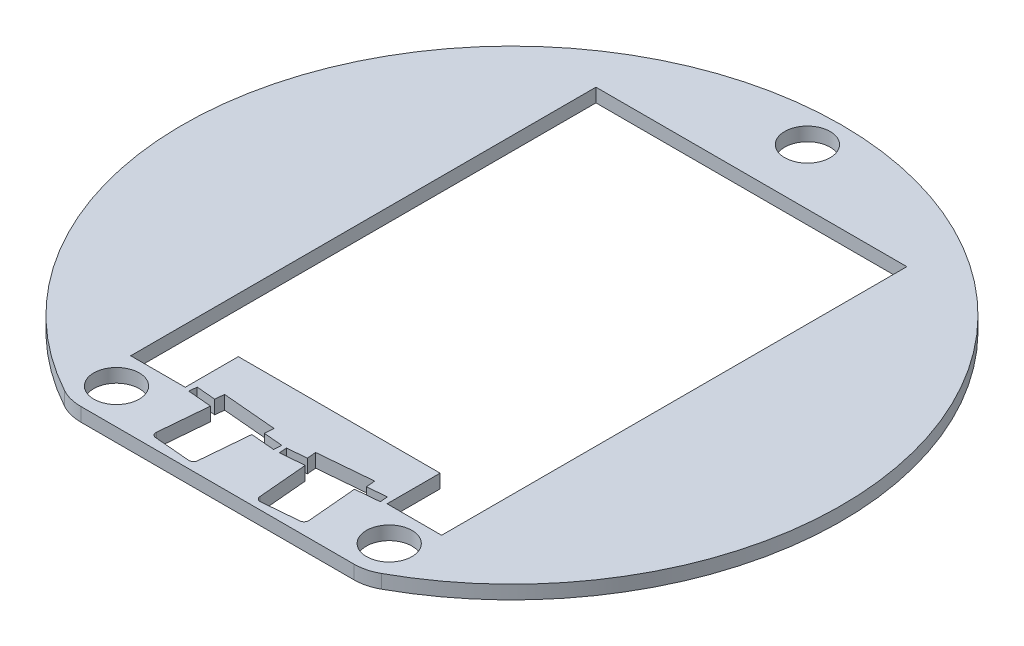
SolidWorks part; units mm, degrees
ref_plane "Front Plane" through (0, 0, 0) normal (0, 0, 1) x (1, 0, 0)
ref_plane "Top Plane" through (0, 0, 0) normal (0, 1, 0) x (1, 0, 0)
ref_plane "Right Plane" through (0, 0, 0) normal (1, 0, 0) x (0, 0, -1)
sketch "Sketch1" plane through (0, 0, 0) normal (0, 1, 0) x (1, 0, 0)
  line L0 (-30.03, -64.8129) -> (30.03, -64.8129)
  line L1 (0, -85) -> (0, 0) construction
  line L2 (0, -85) -> (32.4891, -64.8129) construction
  arc A0 (34.8348, -63.5829) -> (-34.8348, -63.5829) centre (0, 0) ccw
  circle A1 centre (0, -85) radius 38.25 construction
  arc A2 (30.03, -64.8129) -> (34.8348, -63.5829) centre (30.03, -54.8129) ccw
  arc A3 (-30.03, -64.8129) -> (-34.8348, -63.5829) centre (-30.03, -54.8129) cw
  dimension "D1" = 145
  dimension "D2" = 76.5
  dimension "D4" = 10
  dimension "D3" = 85
extrude "Boss-Extrude1" add sketch "Sketch1" along normal blind 3
sketch "Sketch2" plane through (0, 3, 0) normal (0, 1, 0) x (1, 0, 0)
  line L29 (-22.2, -49.6757) -> (-22.2, -32.5) construction
  line L30 (-22.2, -49.6757) -> (-22.2, -32.5) construction
  line L38 (-34.2, -49.6757) -> (-22.2, -49.6757) construction
  line L39 (-34.2, -49.6757) -> (-34.2, 49.6757) construction
  line L40 (-34.2, 49.6757) -> (-22.2, 49.6757) construction
  line L41 (-22.2, 32.5) -> (-22.2, 49.6757) construction
  line L47 (22.2, 32.5) -> (22.2, 49.6757) construction
  line L48 (34.2, 49.6757) -> (22.2, 49.6757) construction
  line L49 (34.2, -49.6757) -> (34.2, 49.6757) construction
  line L50 (34.2, -49.6757) -> (22.2, -49.6757) construction
  line L51 (22.2, -49.6757) -> (22.2, -32.5) construction
  line L52 (22.2, -49.6757) -> (22.2, -32.5) construction
  line L53 (-22.2, -49.6757) -> (-22.2, -38) construction
  line L54 (-22.2, -49.6757) -> (-22.2, -38)
  line L55 (-22.2, 44) -> (22.2, 44)
  line L62 (-34.2, -49.6757) -> (-22.2, -49.6757)
  line L63 (-34.2, -49.6757) -> (-34.2, 49.6757)
  line L64 (-34.2, 49.6757) -> (-22.2, 49.6757)
  line L65 (-22.2, 44) -> (-22.2, 49.6757)
  line L71 (22.2, 44) -> (22.2, 49.6757)
  line L72 (34.2, 49.6757) -> (22.2, 49.6757)
  line L73 (34.2, -49.6757) -> (34.2, 49.6757)
  line L74 (34.2, -49.6757) -> (22.2, -49.6757)
  line L75 (22.2, -49.6757) -> (22.2, -38) construction
  line L76 (22.2, -49.6757) -> (22.2, -38)
  line L77 (-22.2, -38) -> (22.2, -38)
  dimension "D1" = 38
  dimension "D2" = 44
extrude "Cut-Extrude1" cut sketch "Sketch2" against normal through all
sketch "Sketch3" plane through (0, 3, 0) normal (0, 1, 0) x (1, 0, 0)
  line L0 (-34.2, 35) -> (-34.2, -35)
  line L1 (-72.5, -35) -> (-34.2, -35)
  line L2 (-72.5, -35) -> (-72.5, 35)
  line L3 (-72.5, 35) -> (-34.2, 35)
  line L4 (72.5, -35) -> (72.5, 35)
  line L5 (-72.5, -35) -> (72.5, 35) construction
  line L6 (-72.5, 35) -> (72.5, -35) construction
  line L8 (34.2, 35) -> (34.2, -35)
  line L10 (34.2, 35) -> (72.5, 35)
  line L11 (34.2, -35) -> (72.5, -35)
  line L12 (-34.2, -49.6757) -> (-34.2, 49.6757) construction
  line L13 (34.2, -49.6757) -> (34.2, 49.6757) construction
  arc A0 (34.8348, -63.5829) -> (-34.8348, -63.5829) centre (0, 0) ccw construction
  point P0 (0, 0)
  dimension "D1" = 70
sketch "Sketch4" plane through (0, 3, 0) normal (0, 1, 0) x (1, 0, 0)
  line L0 (-21.0702, -50.0262) -> (-0.6482, -51.8129)
  line L1 (21.0702, -50.0262) -> (20.922, -48.3326)
  line L2 (0.6482, -51.8129) -> (0.5, -50.1193)
  line L3 (20.922, -48.3326) -> (0.5, -50.1193)
  line L4 (0, 0) -> (0, -64.8129) construction
  line L5 (-30.03, -64.8129) -> (30.03, -64.8129) construction
  line L6 (-20.922, -48.3326) -> (-0.5, -50.1193)
  line L7 (-0.6482, -51.8129) -> (-0.5, -50.1193)
  line L8 (-21.0702, -50.0262) -> (-20.922, -48.3326)
  line L14 (21.0702, -50.0262) -> (0.6482, -51.8129)
  dimension "D1" = 1.7
  dimension "D2" = 20.5
  dimension "D3" = 5
  dimension "D4" = 13
  dimension "D5" = 0.5
extrude "Cut-Extrude3" cut sketch "Sketch4" against normal through all
sketch "Sketch5" plane through (0, 3, 0) normal (0, 1, 0) x (1, 0, 0)
  line L0 (5.8782, -51.3553) -> (15.8401, -50.4837)
  line L1 (5.8782, -51.3553) -> (6.8369, -62.3134)
  line L2 (15.8401, -50.4837) -> (16.7988, -61.4419)
  line L3 (7.9203, -63.2225) -> (15.8898, -62.5252)
  line L4 (0.6482, -51.8129) -> (21.0702, -50.0262) construction
  line L5 (16.6882, -48.7031) -> (4.7338, -49.7489)
  line L6 (16.6882, -48.7031) -> (16.5139, -46.7107)
  line L7 (4.7338, -49.7489) -> (4.5595, -47.7565)
  line L8 (16.5139, -46.7107) -> (4.5595, -47.7565)
  line L9 (20.922, -48.3326) -> (0.5, -50.1193) construction
  line L10 (0, -38) -> (0, -64.8129) construction
  line L12 (-30.03, -64.8129) -> (30.03, -64.8129) construction
  line L13 (-16.5139, -46.7107) -> (-4.5595, -47.7565)
  line L14 (-4.7338, -49.7489) -> (-4.5595, -47.7565)
  line L15 (-16.6882, -48.7031) -> (-16.5139, -46.7107)
  line L16 (-16.6882, -48.7031) -> (-4.7338, -49.7489)
  line L17 (-7.9203, -63.2225) -> (-15.8898, -62.5252)
  line L18 (-15.8401, -50.4837) -> (-16.7988, -61.4419)
  line L19 (-5.8782, -51.3553) -> (-6.8369, -62.3134)
  line L20 (-5.8782, -51.3553) -> (-15.8401, -50.4837)
  line L21 (-22.2, -38) -> (22.2, -38) construction
  arc A0 (16.7988, -61.4419) -> (15.8898, -62.5252) centre (15.8027, -61.529) cw
  arc A1 (6.8369, -62.3134) -> (7.9203, -63.2225) centre (7.8331, -62.2263) ccw
  arc A2 (-6.8369, -62.3134) -> (-7.9203, -63.2225) centre (-7.8331, -62.2263) cw
  arc A3 (-16.7988, -61.4419) -> (-15.8898, -62.5252) centre (-15.8027, -61.529) ccw
  point P14 (10.711, -49.226)
  point P15 (10.711, -49.226)
  point P17 (10.8592, -50.9195)
  point P18 (10.8592, -50.9195)
  point P21 (16.886, -62.4381)
  point P24 (6.9241, -63.3096)
  point P40 (-6.9241, -63.3096)
  point P41 (-16.886, -62.4381)
  dimension "D5" = 1
  dimension "D1" = 12
  dimension "D2" = 10
  dimension "D3" = 12
  dimension "D4" = 2
extrude "Cut-Extrude4" cut sketch "Sketch5" against normal through all
sketch "Sketch6" plane through (0, 3, 0) normal (0, 1, 0) x (1, 0, 0)
  line L2 (-34.2, 49.6757) -> (34.2, 49.6757)
  line L3 (-34.2, 49.6757) -> (-34.2, 52.6757)
  line L4 (-34.2, 52.6757) -> (34.2, 52.6757)
  line L5 (34.2, 49.6757) -> (34.2, 52.6757)
  dimension "D1" = 3
extrude "Cut-Extrude5" cut sketch "Sketch6" against normal through all
sketch "Sketch7" plane through (0, 3, 0) normal (0, 1, 0) x (1, 0, 0)
  circle A1 centre (-30, -57) radius 5
  circle A2 centre (-30, -57) radius 5
  circle A3 centre (30, -57) radius 5
  circle A4 centre (30, -57) radius 5
  dimension "D1" = 0
  dimension "D2" = 0
extrude "Cut-Extrude6" cut sketch "Sketch7" against normal through all
sketch "Sketch8" plane through (0, 3, 0) normal (0, 1, 0) x (1, 0, 0)
  line L10 (-52.7, 37.2865) -> (-52.7, 32.5)
  line L11 (-52.7, 32.5) -> (-43.3, 32.5)
  line L12 (-43.3, 32.5) -> (-43.3, 37.2865)
  line L13 (-43.3, 37.2865) -> (-43.3, 42.7135)
  line L14 (-43.3, 42.7135) -> (-48, 45.4271)
  line L15 (-48, 45.4271) -> (-52.7, 42.7135)
  line L16 (-52.7, 42.7135) -> (-52.7, 37.2865)
  line L17 (-52.7, 37.2865) -> (-52.7, 32.5)
  line L18 (-52.7, 32.5) -> (-43.3, 32.5)
  line L19 (-43.3, 32.5) -> (-43.3, 37.2865)
  line L20 (-43.3, 37.2865) -> (-43.3, 42.7135)
  line L21 (-43.3, 42.7135) -> (-48, 45.4271)
  line L22 (-48, 45.4271) -> (-52.7, 42.7135)
  line L23 (-52.7, 42.7135) -> (-52.7, 37.2865)
  line L24 (44.7, -32.5) -> (35.3, -32.5)
  line L25 (44.7, -37.2865) -> (44.7, -32.5)
  line L26 (44.7, -42.7135) -> (44.7, -37.2865)
  line L31 (40, -45.4271) -> (44.7, -42.7135)
  line L32 (35.3, -42.7135) -> (40, -45.4271)
  line L33 (35.3, -37.2865) -> (35.3, -42.7135)
  line L34 (35.3, -32.5) -> (35.3, -37.2865)
  line L35 (44.7, -32.5) -> (35.3, -32.5)
  line L36 (44.7, -37.2865) -> (44.7, -32.5)
  line L37 (44.7, -42.7135) -> (44.7, -37.2865)
  line L38 (40, -45.4271) -> (44.7, -42.7135)
  line L39 (35.3, -42.7135) -> (40, -45.4271)
  line L40 (35.3, -37.2865) -> (35.3, -42.7135)
  line L41 (35.3, -32.5) -> (35.3, -37.2865)
  line L42 (-35.3, -37.2865) -> (-35.3, -32.5)
  line L43 (-35.3, -32.5) -> (-44.7, -32.5)
  line L44 (-44.7, -32.5) -> (-44.7, -37.2865)
  line L45 (-44.7, -37.2865) -> (-44.7, -42.7135)
  line L46 (-44.7, -42.7135) -> (-40, -45.4271)
  line L47 (-40, -45.4271) -> (-35.3, -42.7135)
  line L48 (-35.3, -42.7135) -> (-35.3, -37.2865)
  line L49 (-35.3, -37.2865) -> (-35.3, -32.5)
  line L50 (-35.3, -32.5) -> (-44.7, -32.5)
  line L51 (-44.7, -32.5) -> (-44.7, -37.2865)
  line L52 (-44.7, -37.2865) -> (-44.7, -42.7135)
  line L53 (-44.7, -42.7135) -> (-40, -45.4271)
  line L54 (-40, -45.4271) -> (-35.3, -42.7135)
  line L55 (-35.3, -42.7135) -> (-35.3, -37.2865)
  line L56 (52.7, 32.5) -> (52.7, 37.2865)
  line L57 (52.7, 37.2865) -> (52.7, 42.7135)
  line L58 (52.7, 42.7135) -> (48, 45.4271)
  line L59 (48, 45.4271) -> (43.3, 42.7135)
  line L60 (43.3, 42.7135) -> (43.3, 37.2865)
  line L61 (43.3, 37.2865) -> (43.3, 32.5)
  line L62 (43.3, 32.5) -> (52.7, 32.5)
  line L63 (52.7, 32.5) -> (52.7, 37.2865)
  line L64 (52.7, 37.2865) -> (52.7, 42.7135)
  line L65 (52.7, 42.7135) -> (48, 45.4271)
  line L66 (48, 45.4271) -> (43.3, 42.7135)
  line L67 (43.3, 42.7135) -> (43.3, 37.2865)
  line L68 (43.3, 37.2865) -> (43.3, 32.5)
  line L69 (43.3, 32.5) -> (52.7, 32.5)
  dimension "D1" = 0
  dimension "D2" = 0
  dimension "D3" = 0
  dimension "D4" = 0
extrude "Cut-Extrude7" [suppressed] cut sketch "Sketch8" against normal through all
sketch "Sketch11" plane through (0, 3, 0) normal (0, 1, 0) x (1, 0, 0)
  line L0 (0, 0) -> (0, 65) construction
  circle A0 centre (0, 65) radius 5
  dimension "D2" = 10
  dimension "D1" = 65
extrude "Cut-Extrude10" cut sketch "Sketch11" against normal through all
sketch "Sketch12" plane through (0, 3, 0) normal (0, 1, 0) x (1, 0, 0)
  line L0 (-30.03, -64.8129) -> (30.03, -64.8129) construction
  line L1 (-1.35, -64.8129) -> (1.35, -64.8129)
  line L2 (-1.35, -64.8129) -> (-1.35, -61.8129)
  line L3 (-1.35, -55.8129) -> (1.35, -55.8129)
  line L4 (1.35, -64.8129) -> (1.35, -61.8129)
  line L5 (-1.35, -59.6129) -> (-3.1, -59.6129)
  line L6 (3.1, -59.6129) -> (1.35, -59.6129)
  line L7 (3.1, -59.6129) -> (3.1, -61.8129)
  line L8 (3.1, -61.8129) -> (1.35, -61.8129)
  line L9 (-3.1, -59.6129) -> (-3.1, -61.8129)
  line L10 (-1.35, -61.8129) -> (-3.1, -61.8129)
  line L11 (-1.35, -59.6129) -> (-1.35, -55.8129)
  line L12 (1.35, -59.6129) -> (1.35, -55.8129)
  point P14 (0, -64.8129)
  point P15 (0, -64.8129)
  dimension "D1" = 3
  dimension "D2" = 9
  dimension "D3" = 2.7
  dimension "D4" = 2.2
  dimension "D5" = 6.2
extrude "Cut-Extrude11" [suppressed] cut sketch "Sketch12" against normal through all
sketch "Sketch13" plane through (0, 3, 0) normal (0, 1, 0) x (1, 0, 0)
  line L0 (0, 0) -> (0, -22.8942) construction
  circle A0 centre (45, -48) radius 1.65
  circle A1 centre (-45, -48) radius 1.65
  circle A2 centre (40, 50) radius 1.65
  circle A3 centre (-40, 50) radius 1.65
  dimension "D3" = 3.3
  dimension "D1" = 48
  dimension "D2" = 45
  dimension "D4" = 40
  dimension "D5" = 50
extrude "Cut-Extrude12" [suppressed] cut sketch "Sketch13" against normal through all
sketch "Sketch14" plane through (0, 0, 0) normal (0, -1, 0) x (1, 0, 0)
  line L8 (-41.543, 56.9759) -> (-42.0754, 56.6031)
  line L9 (-42.0754, 56.6031) -> (-40.0679, 53.736)
  line L10 (-40.0679, 53.736) -> (-36.7913, 56.0303)
  line L11 (-36.7913, 56.0303) -> (-38.7988, 58.8974)
  line L12 (-38.7988, 58.8974) -> (-39.3313, 58.5245)
  line L13 (-39.3313, 58.5245) -> (-40.4784, 60.1629)
  line L14 (-40.4784, 60.1629) -> (-42.6901, 58.6142)
  line L15 (-42.6901, 58.6142) -> (-41.543, 56.9759)
  line L16 (-41.543, 56.9759) -> (-42.0754, 56.6031)
  line L17 (-42.0754, 56.6031) -> (-40.0679, 53.736)
  line L18 (-40.0679, 53.736) -> (-36.7913, 56.0303)
  line L19 (-36.7913, 56.0303) -> (-38.7988, 58.8974)
  line L20 (-38.7988, 58.8974) -> (-39.3313, 58.5245)
  line L21 (-39.3313, 58.5245) -> (-40.4784, 60.1629)
  line L22 (-40.4784, 60.1629) -> (-42.6901, 58.6142)
  line L23 (-42.6901, 58.6142) -> (-41.543, 56.9759)
  line L24 (41.543, 56.9759) -> (42.6901, 58.6142)
  line L25 (42.0754, 56.6031) -> (41.543, 56.9759)
  line L26 (40.0679, 53.736) -> (42.0754, 56.6031)
  line L27 (36.7913, 56.0303) -> (40.0679, 53.736)
  line L28 (38.7988, 58.8974) -> (36.7913, 56.0303)
  line L29 (39.3313, 58.5245) -> (38.7988, 58.8974)
  line L30 (40.4784, 60.1629) -> (39.3313, 58.5245)
  line L31 (42.6901, 58.6142) -> (40.4784, 60.1629)
  line L32 (41.543, 56.9759) -> (42.6901, 58.6142)
  line L33 (42.0754, 56.6031) -> (41.543, 56.9759)
  line L34 (40.0679, 53.736) -> (42.0754, 56.6031)
  line L35 (36.7913, 56.0303) -> (40.0679, 53.736)
  line L36 (38.7988, 58.8974) -> (36.7913, 56.0303)
  line L37 (39.3313, 58.5245) -> (38.7988, 58.8974)
  line L38 (40.4784, 60.1629) -> (39.3313, 58.5245)
  line L39 (42.6901, 58.6142) -> (40.4784, 60.1629)
  dimension "D1" = 0
  dimension "D2" = 0
extrude "Cut-Extrude13" [suppressed] cut sketch "Sketch14" against normal through all
equation "\"smallPulleyTeeth\"= 30"
equation "\"largePulleyTeeth\"= 30"
equation "\"eighthThick\"= 3.0mm"
equation "\"sixteenthThick\" = 1.7mm"
equation "\"quarterThick\"=6.0mm"
equation "\"OD\" = 145mm"
equation "\"puckAngle\" = 60.5deg"
equation "\"puckDiam\" = 76.5mm"
equation "\"axlePress\" = 5.9mm"
equation "\"press\" = 0.2mm"
equation "\"wheelClear\" = 0.3mm"
equation "\"10-32clear\" = 4.8mm"
equation "\"6-32clear\" = 3.3mm"
equation "\"8-32clear\" = 4.0mm"
equation "\"4-40clear\" = 3.0mm"
equation "\"wheelHeight\" = 22mm"
equation "\"wheelWell\" = 65mm"
equation "\"D1@Sketch1\"=\"OD\""
equation "\"D1@Boss-Extrude1\"=\"eighthThick\""
equation "\"D2@Sketch1\"=\"puckDiam\""
equation "\"puckDist\" = 85mm"
equation "\"scoopFillet\" = 5mm"
equation "\"10-32tap\" = 4.45mm"
equation "\"ledSmall\" = 3.1mm"
equation "\"ledLarge\" = 4.2mm"
equation "\"ledLength\" = 4.2mm"
equation "\"D3@Sketch1\"=\"puckDist\""
equation "\"4-40close\" = 2.7mm"
equation "\"4-40nutThick\" = 2.2mm"
equation "\"4-40nutWidth\" = 6.2mm"
equation "\"D3@Sketch12\"=\"4-40close\""
equation "\"D4@Sketch12\"=\"4-40nutThick\""
equation "\"D5@Sketch12\"=\"4-40nutWidth\""
equation "\"D3@Sketch13\"=\"6-32clear\""
equation "\"D1@Sketch6\"=\"eighthThick\""
